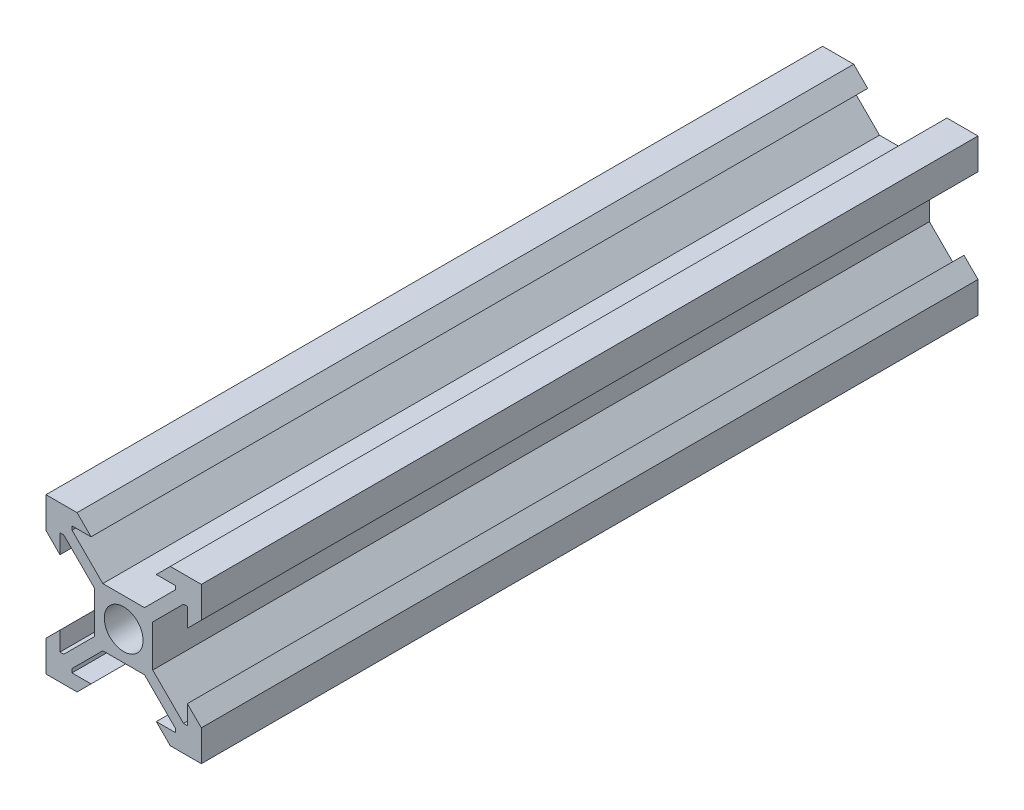
SolidWorks part; units mm, degrees
material "1060 Alloy"
ref_plane "Front Plane" through (0, 0, 0) normal (0, 0, 1) x (1, 0, 0)
ref_plane "Top Plane" through (0, 0, 0) normal (0, 1, 0) x (1, 0, 0)
ref_plane "Right Plane" through (0, 0, 0) normal (1, 0, 0) x (0, 0, -1)
sketch "Sketch1" plane through (0, 0, 0) normal (0, 0, 1) x (1, 0, 0)
  line L0 (-6, 10) -> (-4.2, 8.2)
  line L1 (-10, 10) -> (-6, 10)
  line L2 (-10, 10) -> (-10, 6)
  line L3 (-10, -10) -> (-6, -10)
  line L4 (10, 10) -> (10, 0)
  line L5 (8.2, 4.2) -> (8.2, 6.65)
  line L7 (-2.684, 3.7446) -> (2.684, 3.7446)
  line L8 (-3.7446, 2.684) -> (-3.7446, -2.684)
  line L9 (-2.684, -3.7446) -> (2.684, -3.7446)
  line L10 (3.7446, 2.684) -> (3.7446, -2.684)
  line L11 (-1.7678, 1.7678) -> (1.7678, -1.7678) construction
  line L12 (-1.7678, -1.7678) -> (1.7678, 1.7678) construction
  line L13 (-4.2, 8.2) -> (-6.6526, 8.2)
  line L14 (-7.7107, 6.65) -> (-3.7446, 2.684)
  line L15 (-1.7678, 1.7678) -> (1.7678, -1.7678) construction
  line L16 (-2.684, 3.7446) -> (2.684, 3.7446)
  line L17 (8.2, 6.65) -> (7.7107, 6.65)
  line L18 (7.7107, 6.65) -> (3.7446, 2.684)
  line L19 (6.6526, 7.7133) -> (2.684, 3.7446)
  line L20 (4.2, 8.2) -> (6, 10)
  line L21 (6, 10) -> (10, 10)
  line L22 (10, 6) -> (8.2, 4.2)
  line L23 (6.6526, 8.2) -> (6.6526, 7.7133)
  line L24 (4.2, 8.2) -> (6.6526, 8.2)
  line L25 (6, 10) -> (10, 10)
  line L26 (-10, 6) -> (-8.2, 4.2)
  line L27 (-8.2, 4.2) -> (-8.2, 6.65)
  line L28 (-6, -10) -> (-4.2, -8.2)
  line L29 (-6.6526, 7.7133) -> (-2.684, 3.7446)
  line L31 (0, 0) -> (18.3263, 0) construction
  line L32 (0, 0) -> (-13.5808, 0) construction
  line L33 (-4.2, -8.2) -> (-6.6526, -8.2)
  line L34 (-6.6526, -8.2) -> (-6.6526, -7.7133)
  line L35 (-6.6526, 8.2) -> (-6.6526, 7.7133)
  line L36 (-8.2, 6.65) -> (-7.7107, 6.65)
  line L37 (-6.6526, -7.7133) -> (-2.684, -3.7446)
  line L38 (-7.7107, -6.65) -> (-3.7446, -2.684)
  line L39 (-8.2, -6.65) -> (-7.7107, -6.65)
  line L40 (-8.2, -4.2) -> (-8.2, -6.65)
  line L41 (-10, -6) -> (-8.2, -4.2)
  line L42 (6.6526, -8.2) -> (6.6526, -7.7133)
  line L43 (4.2, -8.2) -> (6.6526, -8.2)
  line L44 (4.2, -8.2) -> (6, -10)
  line L45 (6, -10) -> (10, -10)
  line L46 (10, -6) -> (8.2, -4.2)
  line L47 (8.2, -6.65) -> (7.7107, -6.65)
  line L48 (8.2, -4.2) -> (8.2, -6.65)
  line L49 (6.6526, -7.7133) -> (2.684, -3.7446)
  line L50 (7.7107, -6.65) -> (3.7446, -2.684)
  line L51 (-10, -6) -> (-10, -10)
  line L52 (6, -10) -> (10, -10)
  line L53 (10, -6) -> (10, -10)
  circle A0 centre (0, 0) radius 2.5
  point P0 (0, 0)
  dimension "D3" = 5
  dimension "D8" = 3.7446
  dimension "D1" = 20
  dimension "D2" = 20
  dimension "D4" = 4
  dimension "D5" = 4
  dimension "D6" = 4
  dimension "D7" = 4
  dimension "D9" = 3.7446
  dimension "D10" = 2.684
  dimension "D11" = 1.8
  dimension "D12" = 6.65
  dimension "D13" = 7.7133
  dimension "D15" = 0.75
  dimension "D16" = 1.5
  dimension "D17" = 2.8284
extrude "Boss-Extrude1" add sketch "Sketch1" along normal blind 100 contours L53 L46 L48 L47 L50 L10 L18 L17 L5 L22 L4 L21 L20 L24 L23 L19 L7 L29 L35 L13 L0 L1 L2 L26 L27 L36 L14 L8 L38 L39 L40 L41 L51 L3 L28 L33 L34 L37 L9 L49 L42 L43 L44 L45 A0
